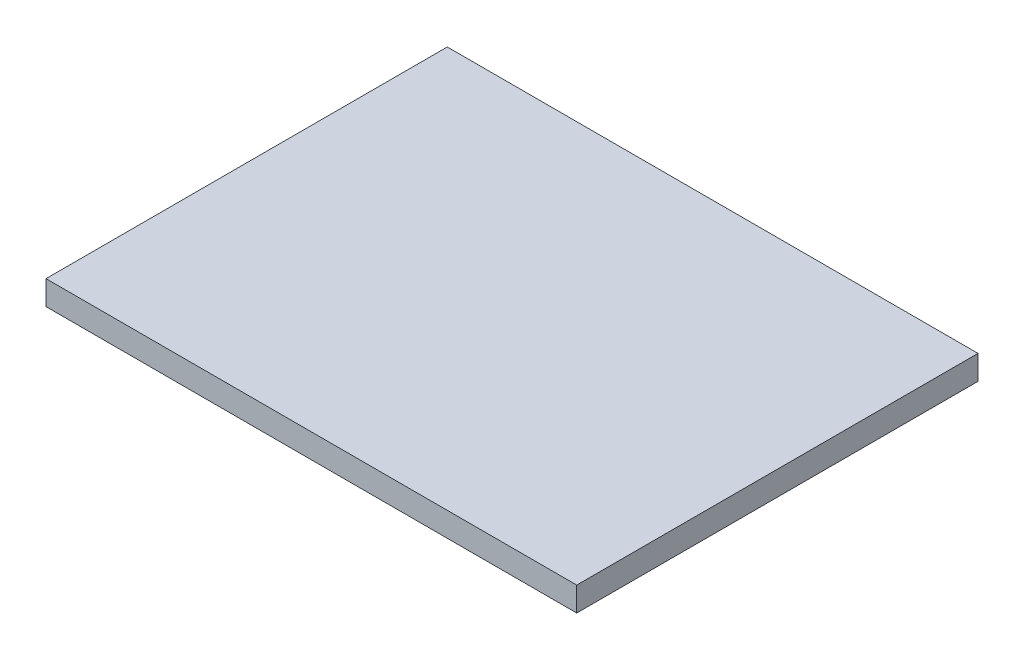
SolidWorks part; units mm, degrees
ref_plane "Front Plane" through (0, 0, 0) normal (0, 0, 1) x (1, 0, 0)
ref_plane "Top Plane" through (0, 0, 0) normal (0, 1, 0) x (1, 0, 0)
ref_plane "Right Plane" through (0, 0, 0) normal (1, 0, 0) x (0, 0, -1)
sketch "Sketch1" plane through (0, 0, 0) normal (0, 1, 0) x (1, 0, 0)
  line L1 (0, 0) -> (260.35, 0)
  line L2 (0, 0) -> (0, 196.85)
  line L3 (0, 196.85) -> (260.35, 196.85)
  line L4 (260.35, 0) -> (260.35, 196.85)
  dimension "D1" = 260.35
  dimension "D2" = 196.85
extrude "Boss-Extrude1" add sketch "Sketch1" along normal blind 11.8872
